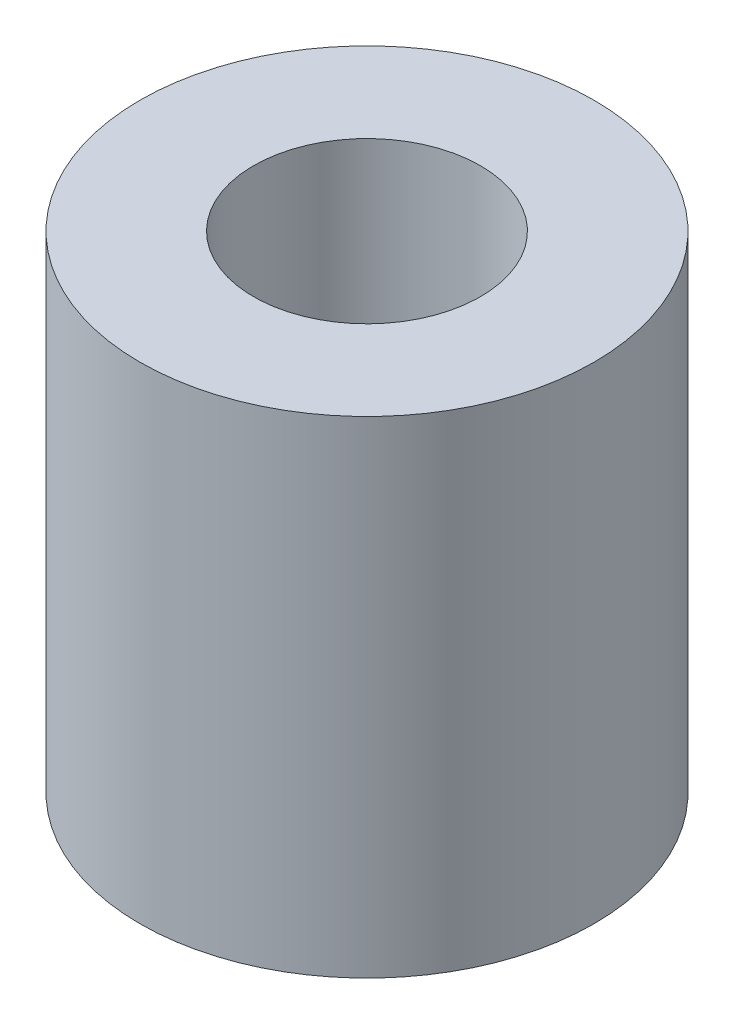
SolidWorks part; units mm, degrees
material "1023 Carbon Steel Sheet (SS)"
ref_plane "Front Plane" through (0, 0, 0) normal (0, 0, 1) x (1, 0, 0)
ref_plane "Top Plane" through (0, 0, 0) normal (0, 1, 0) x (1, 0, 0)
ref_plane "Right Plane" through (0, 0, 0) normal (1, 0, 0) x (0, 0, -1)
sketch "Sketch1" plane through (0, 0, 0) normal (0, 0, 1) x (1, 0, 0)
  line L0 (0, 0) -> (0, 6.1271) construction
  line L1 (-14, 0) -> (-14, 30)
  line L2 (-14, 30) -> (-7, 30)
  line L3 (-7, 30) -> (-7, 0)
  line L4 (-7, 0) -> (-14, 0)
  point P6 (-7, 1.9555)
  dimension "D1" = 14
  dimension "D2" = 28
  dimension "D3" = 30
revolve "Revolve1" add sketch "Sketch1" angle 360 about L0
cosmetic thread "Cosmetic Thread1" parameters "D2"=16
